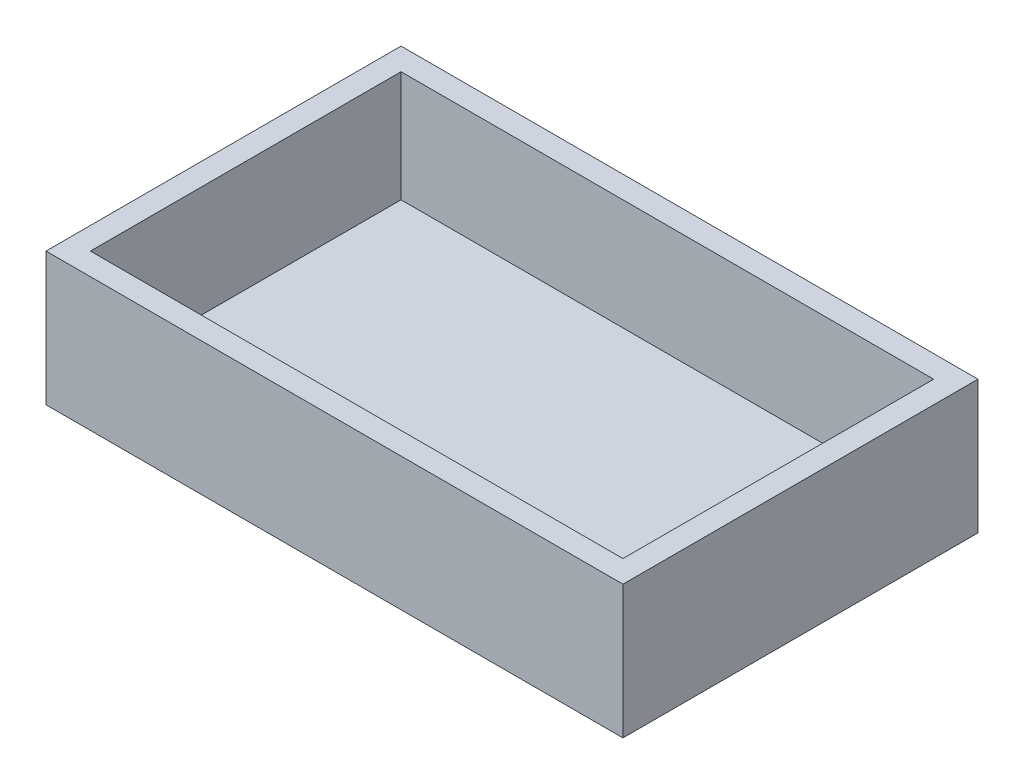
SolidWorks part; units mm, degrees
ref_plane "Front Plane" through (0, 0, 0) normal (0, 0, 1) x (1, 0, 0)
ref_plane "Top Plane" through (0, 0, 0) normal (0, 1, 0) x (1, 0, 0)
ref_plane "Right Plane" through (0, 0, 0) normal (1, 0, 0) x (0, 0, -1)
sketch "Sketch1" plane through (0, 0, 0) normal (0, 1, 0) x (1, 0, 0)
  line L1 (-65, 40) -> (65, 40)
  line L2 (-65, 40) -> (-65, -40)
  line L3 (-65, -40) -> (65, -40)
  line L4 (65, 40) -> (65, -40)
  line L5 (-65, 40) -> (65, -40) construction
  line L6 (-65, -40) -> (65, 40) construction
  point P0 (0, 0)
  dimension "D1" = 130
  dimension "D2" = 80
extrude "Boss-Extrude1" add sketch "Sketch1" along normal blind 5
sketch "Sketch2" plane through (0, 5, 0) normal (0, 1, 0) x (1, 0, 0)
  line L0 (65, 40) -> (-65, 40) construction
  line L1 (60, -35) -> (-60, -35)
  line L2 (60, -35) -> (60, 35)
  line L3 (60, 35) -> (-60, 35)
  line L4 (-60, -35) -> (-60, 35)
  line L5 (60, -35) -> (-60, 35) construction
  line L6 (60, 35) -> (-60, -35) construction
  line L7 (65, -40) -> (65, 40) construction
  line L10 (65, -40) -> (-65, -40)
  line L11 (65, -40) -> (65, 40)
  line L12 (65, 40) -> (-65, 40)
  line L13 (-65, -40) -> (-65, 40)
  line L14 (65, -40) -> (-65, 40) construction
  line L15 (65, 40) -> (-65, -40) construction
  point P0 (0, 0)
  point P10 (0, 0)
  dimension "D1" = 5
  dimension "D2" = 5
extrude "Boss-Extrude2" add sketch "Sketch2" along normal blind 25
sketch "Sketch3" plane through (65, 0, 0) normal (1, 0, 0) x (0, 0, -1)
  line L0 (40, 30) -> (36.0864, 30) construction
  line L1 (-40, 30) -> (40, 30) construction
